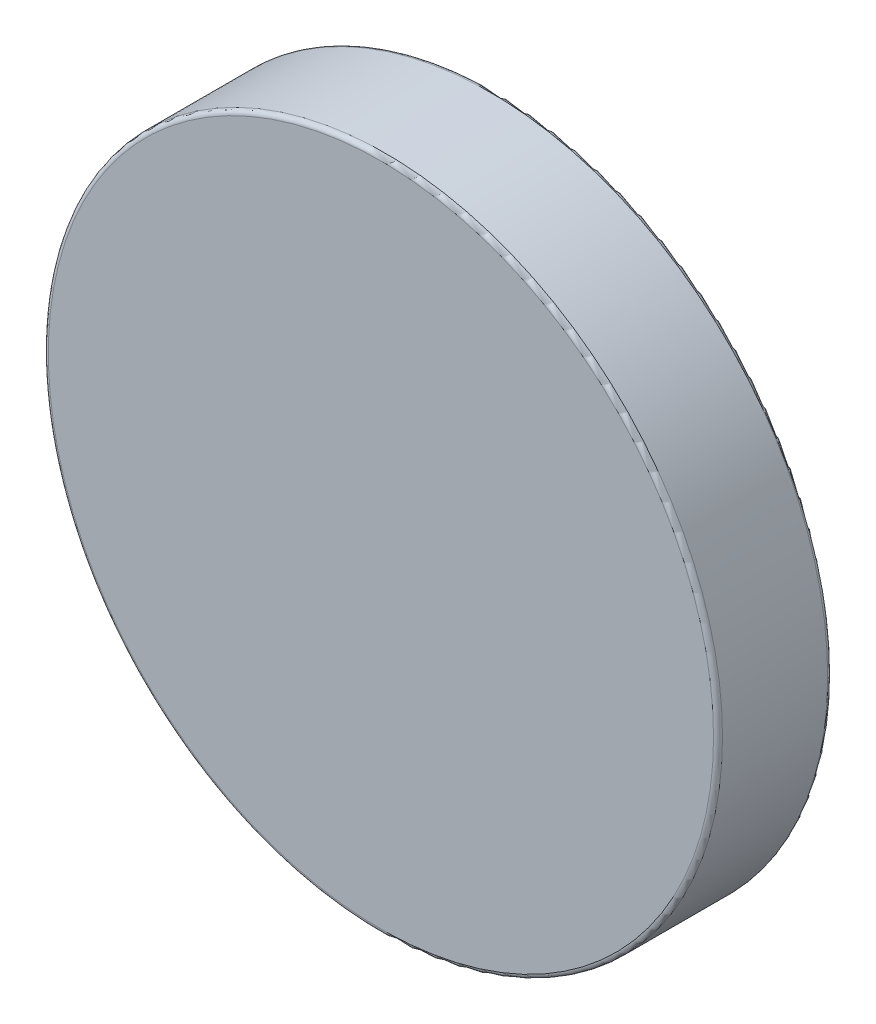
SolidWorks part; units mm, degrees
ref_plane "Plan de face" through (0, 0, 0) normal (0, 0, 1) x (1, 0, 0)
ref_plane "Plan de dessus" through (0, 0, 0) normal (0, 1, 0) x (1, 0, 0)
ref_plane "Plan de droite" through (0, 0, 0) normal (1, 0, 0) x (0, 0, -1)
sketch "Esquisse1" plane through (0, 0, 0) normal (0, 0, 1) x (1, 0, 0)
  circle A0 centre (0, 0) radius 75
  dimension "D1" = 150
extrude "Boss.-Extru.1" add sketch "Esquisse1" along normal blind 25.4
fillet "Congé1" radius 1 1 edges at (75, 0, 25.4)
fillet "Congé2" radius 1 1 edges at (75, 0, 0)
